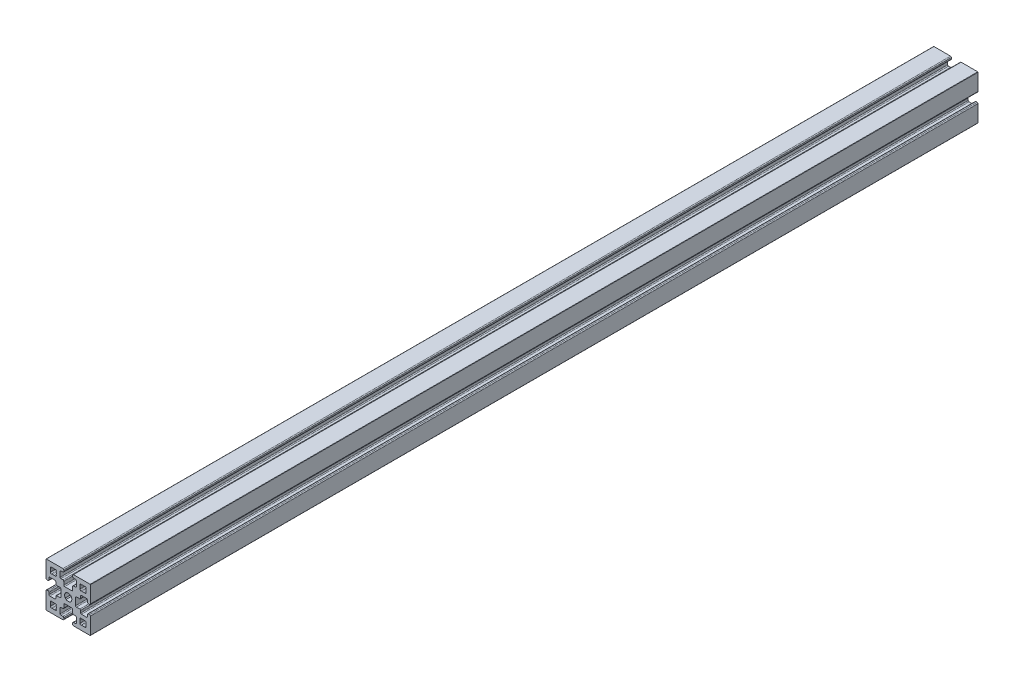
SolidWorks part; units mm, degrees
material "6061 Alloy"
ref_plane "Front Plane" through (0, 0, 0) normal (0, 0, 1) x (1, 0, 0)
ref_plane "Top Plane" through (0, 0, 0) normal (0, 1, 0) x (1, 0, 0)
ref_plane "Right Plane" through (0, 0, 0) normal (1, 0, 0) x (0, 0, -1)
ref_plane "Plane4" through (7.5, 0, 0) normal (1, 0, 0) x (0, 0, -1)
sketch "Sketch1" plane through (7.5, 0, 0) normal (1, 0, 0) x (0, 0, -1)
  line L0 (-5, 7.5) -> (-5, -7.5)
  line L1 (-5, -7.5) -> (495, -7.5)
  line L2 (495, -7.5) -> (495, 7.5)
  line L3 (495, 7.5) -> (-5, 7.5)
  dimension "D1" = 500
extrude "Boss-Extrude1" add sketch "Sketch1" against normal blind 15
sketch "Sketch2" plane through (0, 0, 5) normal (0, 0, 1) x (1, 0, 0)
  line L0 (-7.5, 1.5) -> (-7.5, -1.5)
  line L1 (-7.5, -1.5) -> (-6.5, -1.5)
  line L2 (-6.5, -1.5) -> (-6.5, -2.75)
  line L3 (-6.5, -2.75) -> (-4.2, -2.75)
  line L4 (-4.2, -2.75) -> (-4.2, -1.5)
  line L5 (-4.2, -1.5) -> (-2.5, -1.5)
  line L6 (-2.5, -1.5) -> (-2.5, 1.5)
  line L7 (-2.5, 1.5) -> (-7.5, 1.5)
extrude "Cut-Extrude1" cut sketch "Sketch2" against normal through all
sketch "Sketch3" plane through (0, 0, 5) normal (0, 0, 1) x (1, 0, 0)
  line L0 (-6.5, 1.5) -> (-4.2, 1.5)
  line L1 (-4.2, 1.5) -> (-4.2, 2.75)
  line L2 (-4.2, 2.75) -> (-6.5, 2.75)
  line L3 (-6.5, 2.75) -> (-6.5, 1.5)
extrude "Cut-Extrude2" cut sketch "Sketch3" against normal through all
sketch "Sketch4" plane through (0, 0, 5) normal (0, 0, 1) x (1, 0, 0)
  line L0 (1.5, 7.5) -> (-1.5, 7.5)
  line L1 (-1.5, 7.5) -> (-1.5, 6.5)
  line L2 (-1.5, 6.5) -> (-2.75, 6.5)
  line L3 (-2.75, 6.5) -> (-2.75, 4.2)
  line L4 (-2.75, 4.2) -> (-1.5, 4.2)
  line L5 (-1.5, 4.2) -> (-1.5, 2.5)
  line L6 (-1.5, 2.5) -> (1.5, 2.5)
  line L7 (1.5, 2.5) -> (1.5, 7.5)
extrude "Cut-Extrude3" cut sketch "Sketch4" against normal through all
sketch "Sketch5" plane through (0, 0, 5) normal (0, 0, 1) x (1, 0, 0)
  line L0 (1.5, 6.5) -> (1.5, 4.2)
  line L1 (1.5, 4.2) -> (2.75, 4.2)
  line L2 (2.75, 4.2) -> (2.75, 6.5)
  line L3 (2.75, 6.5) -> (1.5, 6.5)
extrude "Cut-Extrude4" cut sketch "Sketch5" against normal through all
sketch "Sketch6" plane through (0, 0, 5) normal (0, 0, 1) x (1, 0, 0)
  line L0 (7.5, -1.5) -> (7.5, 1.5)
  line L1 (7.5, 1.5) -> (6.5, 1.5)
  line L2 (6.5, 1.5) -> (6.5, 2.75)
  line L3 (6.5, 2.75) -> (4.2, 2.75)
  line L4 (4.2, 2.75) -> (4.2, 1.5)
  line L5 (4.2, 1.5) -> (2.5, 1.5)
  line L6 (2.5, 1.5) -> (2.5, -1.5)
  line L7 (2.5, -1.5) -> (7.5, -1.5)
extrude "Cut-Extrude5" cut sketch "Sketch6" against normal through all
sketch "Sketch7" plane through (0, 0, 5) normal (0, 0, 1) x (1, 0, 0)
  line L0 (6.5, -1.5) -> (4.2, -1.5)
  line L1 (4.2, -1.5) -> (4.2, -2.75)
  line L2 (4.2, -2.75) -> (6.5, -2.75)
  line L3 (6.5, -2.75) -> (6.5, -1.5)
extrude "Cut-Extrude6" cut sketch "Sketch7" against normal through all
sketch "Sketch8" plane through (0, 0, 5) normal (0, 0, 1) x (1, 0, 0)
  line L0 (-1.5, -7.5) -> (1.5, -7.5)
  line L1 (1.5, -7.5) -> (1.5, -6.5)
  line L2 (1.5, -6.5) -> (2.75, -6.5)
  line L3 (2.75, -6.5) -> (2.75, -4.2)
  line L4 (2.75, -4.2) -> (-2.75, -4.2)
  line L5 (-2.75, -4.2) -> (-2.75, -6.5)
  line L6 (-2.75, -6.5) -> (-1.5, -6.5)
  line L7 (-1.5, -6.5) -> (-1.5, -7.5)
extrude "Cut-Extrude7" cut sketch "Sketch8" against normal through all
sketch "Sketch9" plane through (0, 0, 5) normal (0, 0, 1) x (1, 0, 0)
  line L0 (-1.5, -4.2) -> (1.5, -4.2)
  line L1 (1.5, -4.2) -> (1.5, -2.5)
  line L2 (1.5, -2.5) -> (-1.5, -2.5)
  line L3 (-1.5, -2.5) -> (-1.5, -4.2)
extrude "Cut-Extrude8" cut sketch "Sketch9" against normal through all
sketch "Sketch10" plane through (0, 0, -495) normal (0, 0, -1) x (-1, 0, 0)
  circle A0 centre (0, 0) radius 1.2295
extrude "Cut-Extrude9" cut sketch "Sketch10" against normal blind 8
sketch "Sketch11" plane through (0, 0, -487) normal (0, 0, -1) x (-1, 0, 0)
  circle A0 centre (0, 0) radius 1.2295
extrude "Cut-Extrude10" cut sketch "Sketch11" against normal blind 0.1379 draft 59
sketch "Sketch12" plane through (0, 0, -486.8621) normal (0, 0, -1) x (-1, 0, 0)
  circle A0 centre (0, 0) radius 1
extrude "Cut-Extrude11" cut sketch "Sketch12" against normal blind 483.7242
sketch "Sketch13" plane through (0, 0, -3.1379) normal (0, 0, -1) x (-1, 0, 0)
  circle A0 centre (0, 0) radius 1
extrude "Cut-Extrude12" cut sketch "Sketch13" against normal blind 0.1379 draft 59 draft outward yes
sketch "Sketch14" plane through (0, 0, 5) normal (0, 0, 1) x (1, 0, 0)
  circle A0 centre (0, 0) radius 1.2295
extrude "Cut-Extrude13" cut sketch "Sketch14" against normal blind 8
ref_plane "Plane5" through (0, 0.7071, 0) normal (0, -1, 0) x (1, 0, 0)
sketch "Sketch15" plane through (0, 0.7071, 0) normal (0, -1, 0) x (1, 0, 0)
  line L0 (-0.4142, 5) -> (-0.7071, 5)
  line L1 (-0.7071, 5) -> (-0.7071, -495)
  line L2 (-0.7071, -495) -> (-0.4142, -495)
  line L3 (-0.4142, -495) -> (-0.4142, 5)
  line L4 (-0.7071, 5) -> (-0.7071, -495) construction
revolve "Cut-Revolve1" cut sketch "Sketch15" angle 360 about L4
sketch "Sketch16" plane through (0, 0.7071, 0) normal (0, -1, 0) x (1, 0, 0)
  line L0 (1, 5) -> (0.7071, 5)
  line L1 (0.7071, 5) -> (0.7071, -495)
  line L2 (0.7071, -495) -> (1, -495)
  line L3 (1, -495) -> (1, 5)
  line L4 (0.7071, 5) -> (0.7071, -495) construction
revolve "Cut-Revolve2" cut sketch "Sketch16" angle 360 about L4
ref_plane "Plane6" through (0, -0.7071, 0) normal (0, 1, 0) x (1, 0, 0)
sketch "Sketch17" plane through (0, -0.7071, 0) normal (0, 1, 0) x (1, 0, 0)
  line L0 (1, 495) -> (0.7071, 495)
  line L1 (0.7071, 495) -> (0.7071, -5)
  line L2 (0.7071, -5) -> (1, -5)
  line L3 (1, -5) -> (1, 495)
  line L4 (0.7071, 495) -> (0.7071, -5) construction
revolve "Cut-Revolve3" cut sketch "Sketch17" angle 360 about L4
ref_plane "Plane7" through (0, -0.7071, 0) normal (0, -1, 0) x (1, 0, 0)
sketch "Sketch18" plane through (0, -0.7071, 0) normal (0, -1, 0) x (1, 0, 0)
  line L0 (-0.4142, 5) -> (-0.7071, 5)
  line L1 (-0.7071, 5) -> (-0.7071, -495)
  line L2 (-0.7071, -495) -> (-0.4142, -495)
  line L3 (-0.4142, -495) -> (-0.4142, 5)
  line L4 (-0.7071, 5) -> (-0.7071, -495) construction
revolve "Cut-Revolve4" cut sketch "Sketch18" angle 360 about L4
hole_wizard "#1 Clearance Hole1" positions "Sketch20" profile "Sketch19" hole size "#1" standard "ANSI Inch"
sketch "Sketch20" plane through (0, 0, 5) normal (0, 0, 1) x (1, 0, 0)
  point P0 (5, -5)
  point P1 (-5, 5)
  point P2 (5, 5)
  point P3 (-5, -5)
sketch "Sketch19" plane through (5, -5, 5) normal (1, 0, 0) x (0, -1, 0)
  line L0 (0, 0) -> (0, 500)
  line L1 (0, 500) -> (1, 500)
  line L2 (1, 500) -> (1, 0)
  line L5 (1, 0) -> (0, 0)
  line L11 (0, -6.35) -> (0, 107.95) construction
  dimension "Thru Hole Dia." = 2
  dimension "Thru Hole Depth" = 500
hole_wizard "Hole1" positions "Sketch22" profile "Sketch21" legacy
sketch "Sketch22" plane through (0, 0, 5) normal (0, 0, 1) x (1, 0, 0)
  point P0 (4.2929, 4.2929)
  point P1 (5.7071, 4.2929)
  point P2 (4.2929, 5.7071)
  point P3 (5.7071, 5.7071)
  point P4 (-4.2929, -4.2929)
  point P5 (-5.7071, -4.2929)
  point P6 (-4.2929, -5.7071)
  point P7 (-5.7071, -5.7071)
  point P8 (-4.2929, 5.7071)
  point P9 (-4.2929, 4.2929)
  point P10 (-5.7071, 5.7071)
  point P11 (-5.7071, 4.2929)
  point P12 (4.2929, -5.7071)
  point P13 (4.2929, -4.2929)
  point P14 (5.7071, -5.7071)
  point P15 (5.7071, -4.2929)
sketch "Sketch21" plane through (4.2929, 4.2929, 5) normal (1, 0, 0) x (0, -1, 0)
  line L0 (0, 0) -> (0, 500)
  line L1 (0, 500) -> (0.2929, 500)
  line L2 (0.2929, 500) -> (0.2929, 0)
  line L3 (0.2929, 0) -> (0, 0)
  line L4 (0, 110) -> (0, -10) construction
  dimension "Diameter" = 0.5858
  dimension "Depth" = 500
fillet "Fillet1" radius 0.1 4 edges at (-7.5, 7.5, -245) (-7.5, -7.5, -245) (7.5, -7.5, -245) (7.5, 7.5, -245)
fillet "Fillet2" radius 0.3 48 edges at (7.5, -1.5, -245) (-2.75, 6.5, -245) (-2.5, 1.5, -245) (-4.2, 2.75, -245) (6.5, 2.75, -245) (-6.5, 1.5, -245) (2.75, 6.5, -245) (1.5, 7.5, -245) (-6.5, 2.75, -245) (6.5, -2.75, -245) (1.5, -4.2, -245) (-2.75, -4.2, -245) (-1.5, -4.2, -245) (-1.5, -2.5, -245) (-2.75, 4.2, -245) (2.5, -1.5, -245) (-7.5, 1.5, -245) (1.5, 2.5, -245) (4.2, 1.5, -245) (-1.5, -7.5, -245) (2.75, 4.2, -245) (4.2, -2.75, -245) (6.5, 1.5, -245) (2.75, -4.2, -245) (1.5, 6.5, -245) (2.75, -6.5, -245) (-1.5, 4.2, -245) (1.5, -2.5, -245) (1.5, 4.2, -245) (1.5, -7.5, -245) (-4.2, -1.5, -245) (2.5, 1.5, -245) (-4.2, 1.5, -245) (7.5, 1.5, -245) (-6.5, -1.5, -245) (-1.5, 2.5, -245) (-1.5, -6.5, -245) (-2.5, -1.5, -245) (-1.5, 6.5, -245) (-7.5, -1.5, -245) (-4.2, -2.75, -245) (-1.5, 7.5, -245) (4.2, 2.75, -245) (-6.5, -2.75, -245) (-2.75, -6.5, -245) (1.5, -6.5, -245) (6.5, -1.5, -245) (4.2, -1.5, -245)
fillet "Fillet3" radius 0.5 32 edges at (5.8817, 5.4719, -245) (5.4719, 5.8817, -245) (4.5281, 5.8817, -245) (4.1183, 5.4719, -245) (5.4719, -5.8817, -245) (5.8817, -5.4719, -245) (-4.1183, -4.5281, -245) (-4.5281, -4.1183, -245) (-5.8817, -5.4719, -245) (-5.4719, -5.8817, -245) (4.1183, 4.5281, -245) (4.5281, 4.1183, -245) (-5.4719, -4.1183, -245) (-5.8817, -4.5281, -245) (4.1183, -5.4719, -245) (4.5281, -5.8817, -245) (-4.1183, 5.4719, -245) (-4.5281, 5.8817, -245) (4.5281, -4.1183, -245) (4.1183, -4.5281, -245) (-5.8817, 4.5281, -245) (-5.4719, 4.1183, -245) (-5.4719, 5.8817, -245) (-5.8817, 5.4719, -245) (-4.5281, 4.1183, -245) (-4.1183, 4.5281, -245) (5.4719, 4.1183, -245) (5.8817, 4.5281, -245) (5.8817, -4.5281, -245) (5.4719, -4.1183, -245) (-4.5281, -5.8817, -245) (-4.1183, -5.4719, -245)
ref_plane "Plane8" through (0, 0, -295) normal (0, 0, 1) x (1, 0, 0)
split "Split1" trim tools "Plane8" bodies to split 122 resulting bodies 124
ref_plane "Mid Plane" through (0, 0, -145) normal (0, 0, 1) x (1, 0, 0)
